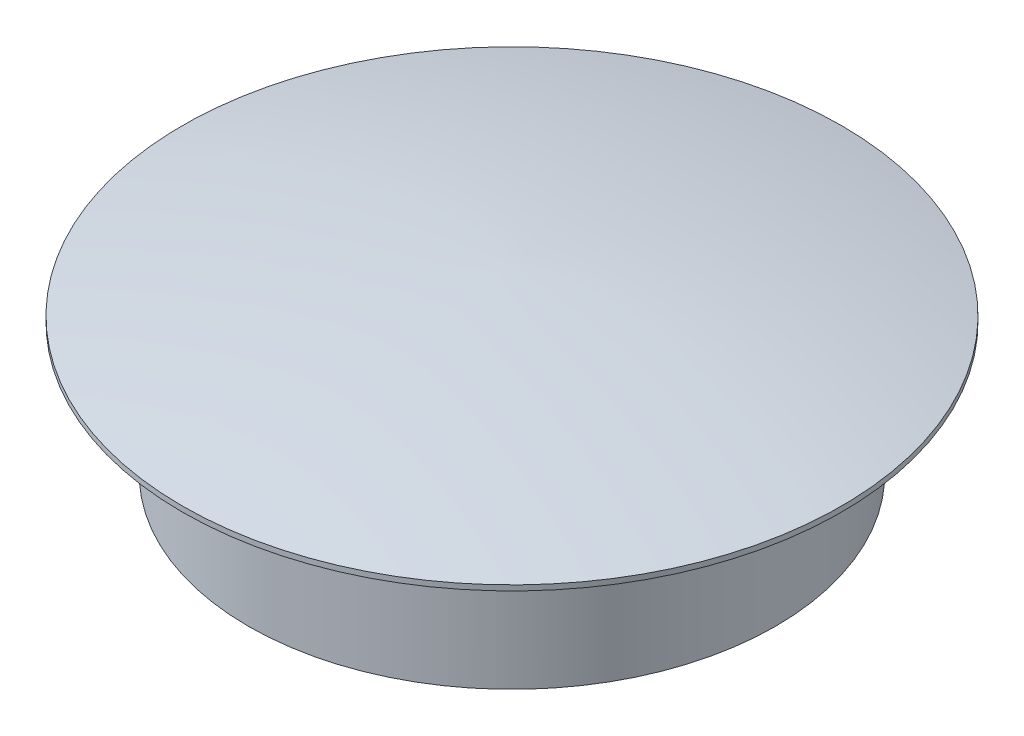
SolidWorks part; units mm, degrees
material "ABS"
ref_plane "Front Plane" through (0, 0, 0) normal (0, 0, 1) x (1, 0, 0)
ref_plane "Top Plane" through (0, 0, 0) normal (0, 1, 0) x (1, 0, 0)
ref_plane "Right Plane" through (0, 0, 0) normal (1, 0, 0) x (0, 0, -1)
sketch "Sketch1" plane through (0, 0, 0) normal (0, 1, 0) x (1, 0, 0)
  circle A0 centre (0, 0) radius 15.875
  dimension "D1" = 31.75
extrude "Boss-Extrude1" add sketch "Sketch1" along normal blind 0.254
sketch "Sketch2" plane through (0, 0, 0) normal (0, -1, 0) x (1, 0, 0)
  line L1 (7.1477, -4.1177) -> (7.1398, 4.1312)
  line L2 (7.1398, 4.1312) -> (-0.0078, 8.2489)
  line L3 (-0.0078, 8.2489) -> (-7.1477, 4.1177)
  line L4 (-7.1477, 4.1177) -> (-7.1398, -4.1312)
  line L5 (-7.1398, -4.1312) -> (0.0078, -8.2489)
  line L6 (0.0078, -8.2489) -> (7.1477, -4.1177)
  circle A0 centre (0, 0) radius 12.7
  circle A1 centre (0, 0) radius 7.1437 construction
  circle A2 centre (0, 0) radius 11.43
  dimension "D1" = 25.4
  dimension "D3" = 22.86
  dimension "D2" = 14.2875
extrude "Boss-Extrude2" add sketch "Sketch2" along normal blind 6.35 contours A0 A2
sketch "Sketch4" plane through (0, 0, 0) normal (0, 0, 1) x (1, 0, 0)
  line L2 (0, 0.254) -> (0, 2.4328)
  line L4 (0, 0.254) -> (15.875, 0.254)
  line L5 (15.875, 0.254) -> (-15.875, 0.254) construction
  arc A1 (0, 2.4328) -> (15.875, 0.254) centre (-2.0518, -71.439) cw
  dimension "D1" = 73.9003
  dimension "D2" = 2.1788
revolve "Revolve1" add sketch "Sketch4" angle 360 about L2
